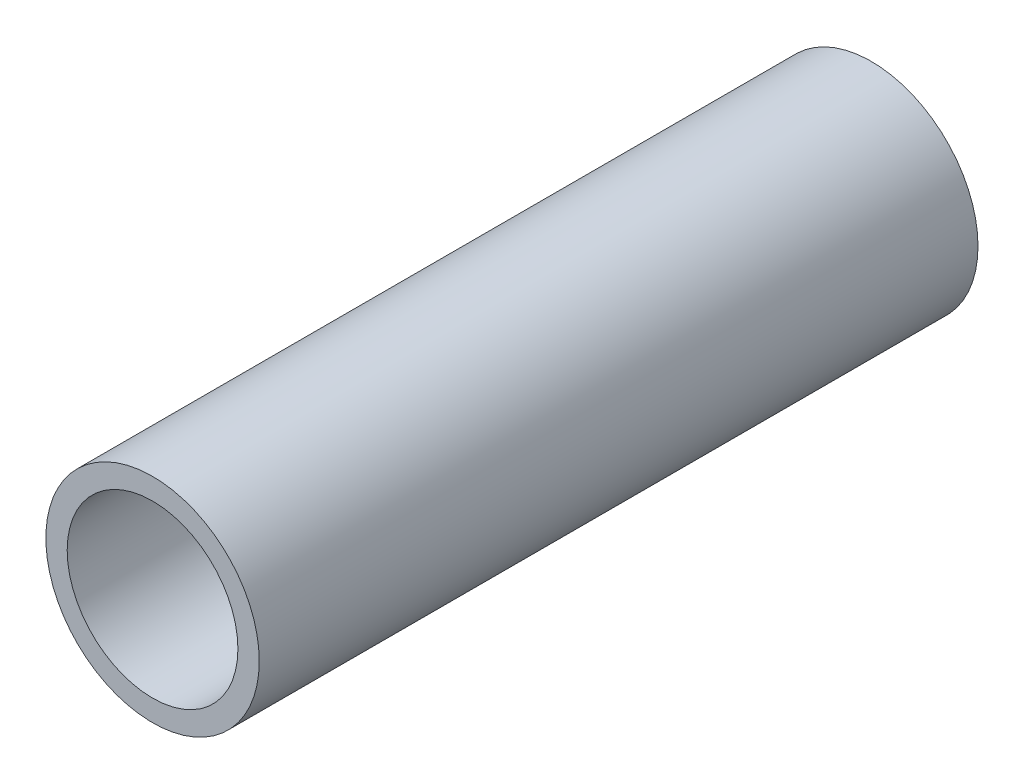
SolidWorks part; units mm, degrees
ref_plane "Front Plane" through (0, 0, 0) normal (0, 0, 1) x (1, 0, 0)
ref_plane "Top Plane" through (0, 0, 0) normal (0, 1, 0) x (1, 0, 0)
ref_plane "Right Plane" through (0, 0, 0) normal (1, 0, 0) x (0, 0, -1)
sketch "Sketch1" plane through (0, 0, 0) normal (0, 0, 1) x (1, 0, 0)
  circle A0 centre (0, 0) radius 1.25
  circle A1 centre (0, 0) radius 1
extrude "Boss-Extrude1" add sketch "Sketch1" along normal blind 8.42
